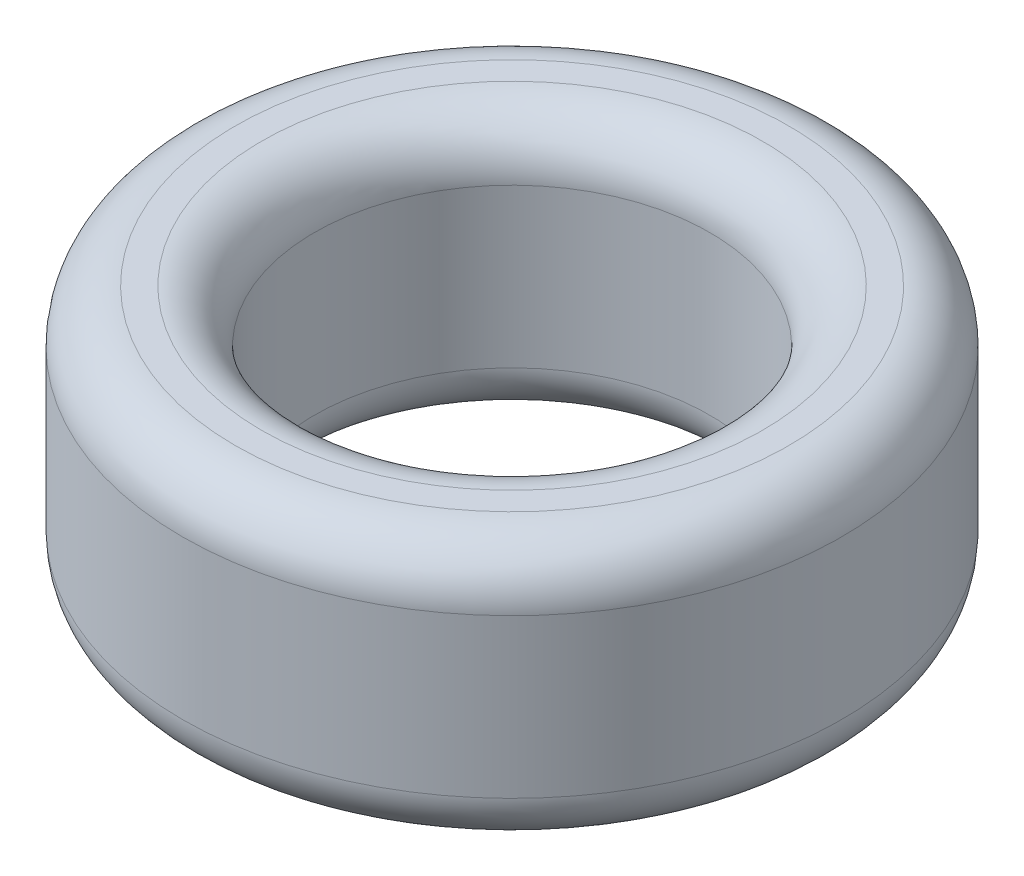
SolidWorks part; units mm, degrees
ref_plane "Front Plane" through (0, 0, 0) normal (0, 0, 1) x (1, 0, 0)
ref_plane "Top Plane" through (0, 0, 0) normal (0, 1, 0) x (1, 0, 0)
ref_plane "Right Plane" through (0, 0, 0) normal (1, 0, 0) x (0, 0, -1)
sketch "Sketch1" plane through (0, 0, 0) normal (0, 1, 0) x (1, 0, 0)
  circle A0 centre (0, 0) radius 12.5
  dimension "D1" = 25
extrude "Boss-Extrude1" add sketch "Sketch1" along normal blind 10
sketch "Sketch2" plane through (0, 10, 0) normal (0, 1, 0) x (1, 0, 0)
  circle A0 centre (0, 0) radius 7.5
  dimension "D1" = 15
extrude "Cut-Extrude1" cut sketch "Sketch2" against normal through all
fillet "Fillet1" radius 2 4 edges at (0, 0, 7.5) (0, 10, 7.5) (0, 0, 12.5) (0, 10, 12.5)
